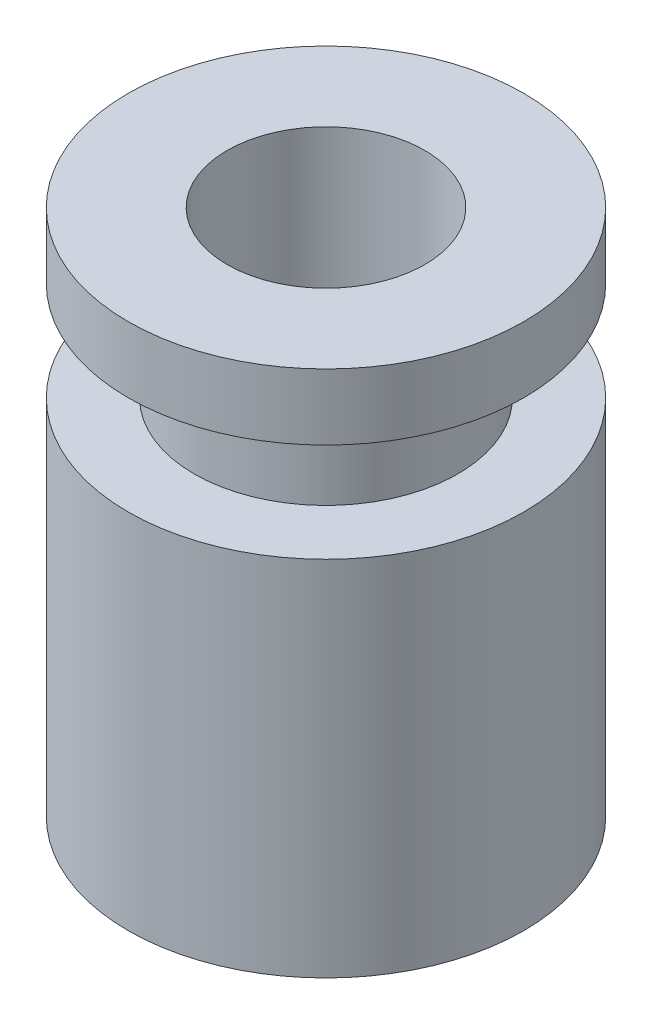
SolidWorks part; units mm, degrees
material "硅橡胶"
ref_plane "前视基准面" through (0, 0, 0) normal (0, 0, 1) x (1, 0, 0)
ref_plane "上视基准面" through (0, 0, 0) normal (0, 1, 0) x (1, 0, 0)
ref_plane "右视基准面" through (0, 0, 0) normal (1, 0, 0) x (0, 0, -1)
other "Configuration Table"
sketch "草图1" plane through (0, 0, 0) normal (0, 1, 0) x (1, 0, 0)
  circle A0 centre (0, 0) radius 3
  circle A1 centre (0, 0) radius 1.5
  dimension "D1" = 6
  dimension "D2" = 3
extrude "凸台-拉伸1" add sketch "草图1" along normal blind 5.5
sketch "草图2" plane through (0, 5.5, 0) normal (0, 1, 0) x (1, 0, 0)
  circle A0 centre (0, 0) radius 2
  circle A1 centre (0, 0) radius 1.5 construction
  circle A2 centre (0, 0) radius 1.5
  dimension "D1" = 4
extrude "凸台-拉伸2" add sketch "草图2" along normal blind 1.5 contours A2 | A0
sketch "草图3" plane through (0, 7, 0) normal (0, 1, 0) x (1, 0, 0)
  circle A1 centre (0, 0) radius 1.5
  circle A2 centre (0, 0) radius 1.5
  circle A3 centre (0, 0) radius 3
  circle A4 centre (0, 0) radius 3
  dimension "D1" = 0
  dimension "D2" = 0
extrude "凸台-拉伸4" add sketch "草图3" along normal blind 1 contours A4
